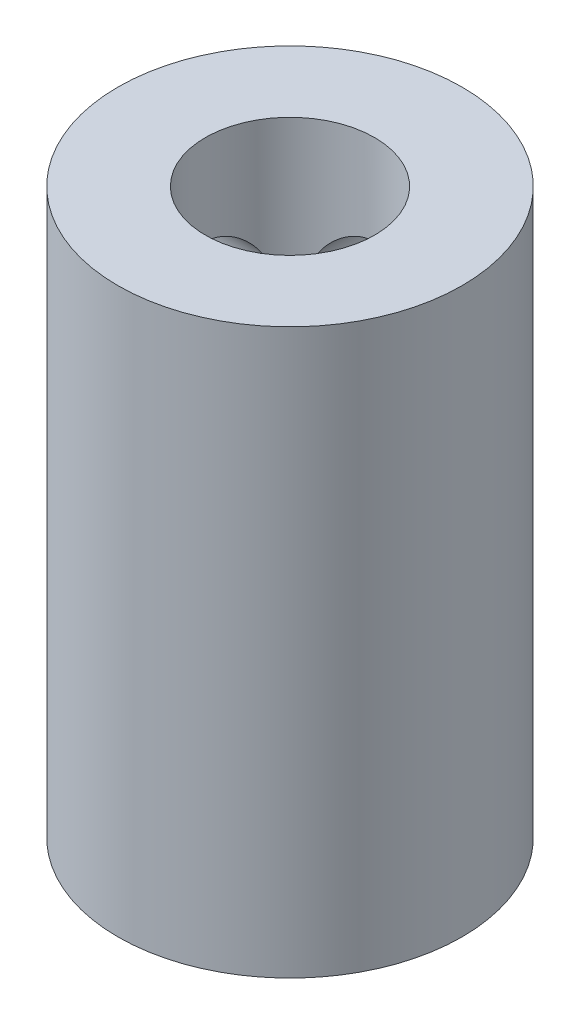
SolidWorks part; units mm, degrees
ref_plane "Alzado" through (0, 0, 0) normal (1, 0, 0) x (0, 1, 0)
ref_plane "Planta" through (0, 0, 0) normal (0, 0, 1) x (0, 1, 0)
ref_plane "Vista lateral" through (0, 0, 0) normal (0, 1, 0) x (-1, 0, 0)
sketch "Croquis1" plane through (0, 0, 0) normal (0, 1, 0) x (-1, 0, 0)
  circle A0 centre (0, 0) radius 6.1
  dimension "D1" = 12.2
extrude "Saliente-Extruir1" add sketch "Croquis1" along normal blind 20
sketch "Croquis2" plane through (0, 20, 0) normal (0, 1, 0) x (-1, 0, 0)
  line L0 (2.5981, 1.5) -> (-2.5981, 1.5)
  line L1 (0, 0) -> (0, 1.5) construction
  arc A0 (-2.5981, 1.5) -> (2.5981, 1.5) centre (0, 0) ccw
  dimension "D1" = 3
  dimension "D2" = 1.5
extrude "Saliente-Extruir2" [suppressed] add sketch "Croquis2" along normal blind 17
sketch "Croquis3" plane through (0, 0, 0) normal (0, -1, 0) x (1, 0, 0)
  circle A0 centre (0, 0) radius 3
  dimension "D1" = 6
extrude "Cortar-Extruir1" cut sketch "Croquis3" against normal through all
sketch "Croquis4" plane through (0, 0, 0) normal (0, 0, 1) x (0, 1, 0)
  line L0 (5, 6.1) -> (5, 0) construction
  line L2 (5, 0) -> (0, 0) construction
  line L3 (10, 6.1) -> (10, -6.1) construction
  line L4 (20, 6.1) -> (0, 6.1) construction
  line L5 (0, -6.1) -> (20, -6.1) construction
  line L6 (5, 0) -> (10, 0) construction
  circle A0 centre (5, 0) radius 1.5
  circle A1 centre (15, 0) radius 1.5
  point P1 (5, 0)
  point P2 (15, 0)
  dimension "D1" = 3
hole_wizard "Taladro de margen para M31" positions "Croquis4" profile "Croquis5" hole size "M3" standard "Ansi Metric"
sketch "Croquis5" plane through (0, 15, 0) normal (1, 0, 0) x (0, -1, 0)
  line L0 (0, 0) -> (0, 6.1)
  line L1 (0, 6.1) -> (1.8, 6.1)
  line L2 (1.8, 6.1) -> (1.8, 0)
  line L5 (1.8, 0) -> (0, 0)
  line L11 (0, -6.35) -> (0, 107.95) construction
  dimension "Diámetro de taladro hasta el siguiente" = 3.6
  dimension "Profundidad de taladro hasta el siguiente" = 6.1
sketch "Croquis6" plane through (0, 0, 0) normal (1, 0, 0) x (0, 1, 0)
  point P0 (5, 0)
  point P1 (15, 0)
hole_wizard "Taladro de margen para M32" positions "Croquis6" profile "Croquis7" hole size "M3" standard "Ansi Metric"
sketch "Croquis7" plane through (0, 5, 0) normal (0, 1, 0) x (0, 0, -1)
  line L0 (0, 0) -> (0, 6.1)
  line L1 (0, 6.1) -> (1.8, 6.1)
  line L2 (1.8, 6.1) -> (1.8, 0)
  line L5 (1.8, 0) -> (0, 0)
  line L11 (0, -6.35) -> (0, 107.95) construction
  dimension "Diámetro de taladro hasta el siguiente" = 3.6
  dimension "Profundidad de taladro hasta el siguiente" = 6.1
equation "\"D2@Croquis2\"=\"D1@Croquis2\"/2"
